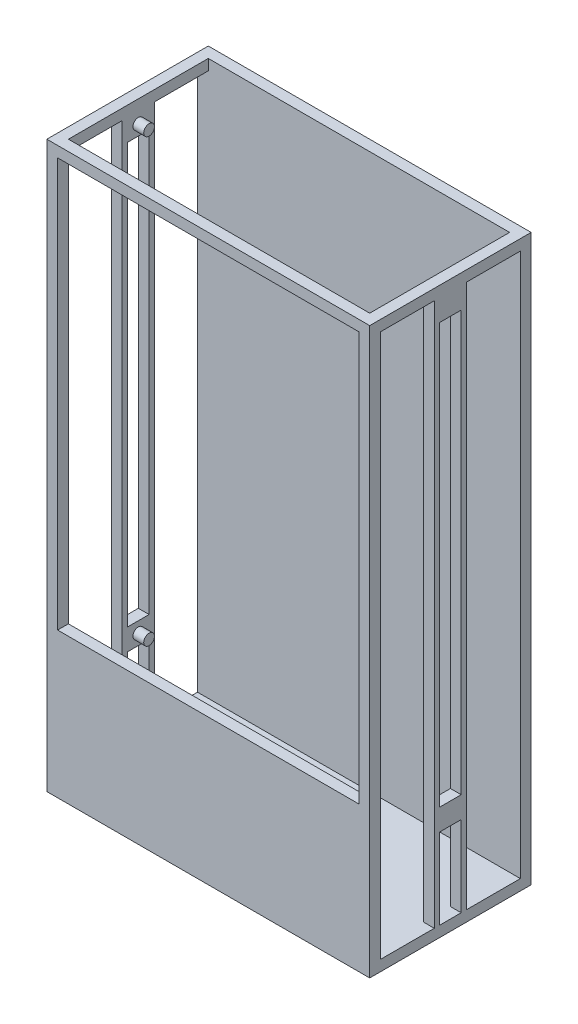
SolidWorks part; units mm, degrees
ref_plane "Front Plane" through (0, 0, 0) normal (0, 0, 1) x (1, 0, 0)
ref_plane "Top Plane" through (0, 0, 0) normal (0, 1, 0) x (1, 0, 0)
ref_plane "Right Plane" through (0, 0, 0) normal (1, 0, 0) x (0, 0, -1)
sketch "Sketch1" plane through (0, 0, 0) normal (0, 0, 1) x (1, 0, 0)
  line L1 (0, 0) -> (3000, 0)
  line L2 (0, 0) -> (0, -5000)
  line L3 (0, -5000) -> (3000, -5000)
  line L4 (3000, 0) -> (3000, -5000)
  dimension "D1" = 5000
  dimension "D2" = 3000
extrude "Boss-Extrude1" add sketch "Sketch1" along normal blind 100
sketch "Sketch2" plane through (0, 0, 100) normal (0, 0, 1) x (1, 0, 0)
  line L0 (0, 0) -> (0, -5000) construction
  line L1 (0, -4900) -> (3000, -4900)
  line L2 (0, -4900) -> (0, -5000)
  line L3 (0, -5000) -> (3000, -5000)
  line L4 (3000, -4900) -> (3000, -5000)
  dimension "D1" = 100
extrude "Boss-Extrude2" add sketch "Sketch2" along normal blind 1400
sketch "Sketch3" plane through (0, -4900, 0) normal (0, 1, 0) x (1, 0, 0)
  line L1 (0, -1500) -> (100, -1500)
  line L2 (0, -1500) -> (0, -1400)
  line L3 (0, -1400) -> (100, -1400)
  line L4 (100, -1500) -> (100, -1400)
  dimension "D1" = 100
  dimension "D2" = 100
extrude "Boss-Extrude3" add sketch "Sketch3" along normal blind 4900
sketch "Sketch4" plane through (0, -4900, 0) normal (0, 1, 0) x (1, 0, 0)
  line L1 (3000, -1500) -> (2900, -1500)
  line L2 (3000, -1500) -> (3000, -1400)
  line L3 (3000, -1400) -> (2900, -1400)
  line L4 (2900, -1500) -> (2900, -1400)
  dimension "D1" = 100
  dimension "D2" = 100
extrude "Boss-Extrude4" add sketch "Sketch4" along normal blind 4900
sketch "Sketch6" plane through (100, 0, 0) normal (1, 0, 0) x (0, 0, -1)
  line L0 (-1500, -5000) -> (-1500, 0) construction
  line L1 (-1400, -4900) -> (-1500, -4900)
  line L2 (-1400, -4900) -> (-1400, -3900)
  line L3 (-1400, -3900) -> (-1500, -3900)
  line L4 (-1500, -4900) -> (-1500, -3900)
  line L5 (-1500, -5000) -> (0, -5000) construction
  dimension "D1" = 1100
extrude "Boss-Extrude5" add sketch "Sketch6" along normal blind 2800
sketch "Sketch22" plane through (3000, 0, 0) normal (1, 0, 0) x (0, 0, -1)
  line L1 (-900, 0) -> (-600, 0)
  line L2 (-900, 0) -> (-900, -4900)
  line L3 (-900, -4900) -> (-600, -4900)
  line L4 (-600, 0) -> (-600, -4900)
  line L6 (-100, -4900) -> (-100, 0) construction
  line L7 (-100, 0) -> (0, 0) construction
  dimension "D1" = 500
  dimension "D2" = 800
  dimension "D3" = 4900
extrude "Boss-Extrude17" add sketch "Sketch22" against normal blind 100
sketch "Sketch23" plane through (0, 0, 0) normal (-1, 0, 0) x (0, 0, 1)
  line L1 (600, 0) -> (900, 0)
  line L2 (600, 0) -> (600, -4900)
  line L3 (600, -4900) -> (900, -4900)
  line L4 (900, 0) -> (900, -4900)
  line L9 (1500, 0) -> (1500, -5000) construction
  line L10 (1400, 0) -> (1500, 0) construction
  dimension "D1" = 600
  dimension "D2" = 900
  dimension "D3" = 4900
extrude "Boss-Extrude18" add sketch "Sketch23" against normal blind 100
sketch "Sketch24" plane through (0, 0, 0) normal (-1, 0, 0) x (0, 0, 1)
  line L1 (650, 0) -> (850, 0)
  line L2 (650, 0) -> (650, -4900)
  line L3 (650, -4900) -> (850, -4900)
  line L4 (850, 0) -> (850, -4900)
  line L8 (1400, 0) -> (1400, -4900) construction
  line L9 (1400, 0) -> (1500, 0) construction
  dimension "D1" = 550
  dimension "D2" = 750
  dimension "D3" = 4900
extrude "Cut-Extrude1" cut sketch "Sketch24" against normal through all
sketch "Sketch25" plane through (0, 0, 0) normal (-1, 0, 0) x (0, 0, 1)
  line L0 (650, 0) -> (650, -4900) construction
  line L1 (650, -4200) -> (850, -4200)
  line L2 (650, -4200) -> (650, -4400)
  line L3 (650, -4400) -> (850, -4400)
  line L4 (850, -4200) -> (850, -4400)
  line L5 (850, -4900) -> (850, 0) construction
  dimension "D1" = 500
extrude "Boss-Extrude19" add sketch "Sketch25" against normal blind 100
sketch "Sketch26" plane through (3000, 0, 0) normal (1, 0, 0) x (0, 0, -1)
  line L1 (-850, -4200) -> (-650, -4200)
  line L2 (-850, -4200) -> (-850, -4400)
  line L3 (-850, -4400) -> (-650, -4400)
  line L4 (-650, -4200) -> (-650, -4400)
extrude "Boss-Extrude20" add sketch "Sketch26" against normal blind 100
sketch "Sketch31" plane through (3000, 0, 0) normal (1, 0, 0) x (0, 0, -1)
  line L0 (-100, -4900) -> (-100, 0) construction
  line L1 (-1400, 0) -> (-100, 0)
  line L2 (-1400, 0) -> (-1400, -100)
  line L3 (-1400, -100) -> (-100, -100)
  line L4 (-100, 0) -> (-100, -100)
  dimension "D1" = 100
extrude "Boss-Extrude23" add sketch "Sketch31" against normal blind 100
sketch "Sketch33" plane through (0, 0, 0) normal (-1, 0, 0) x (0, 0, 1)
  line L1 (100, 0) -> (1400, 0)
  line L2 (100, 0) -> (100, -100)
  line L3 (100, -100) -> (1400, -100)
  line L4 (1400, 0) -> (1400, -100)
extrude "Boss-Extrude24" add sketch "Sketch33" against normal blind 100
sketch "Sketch34" plane through (2900, 0, 0) normal (-1, 0, 0) x (0, 0, 1)
  line L0 (1500, 0) -> (0, 0) construction
  line L1 (1400, 0) -> (1500, 0)
  line L2 (1400, 0) -> (1400, -100)
  line L3 (1400, -100) -> (1500, -100)
  line L4 (1500, 0) -> (1500, -100)
  line L5 (1500, 0) -> (1500, -5000) construction
sketch "Sketch43" plane through (0, 0, 0) normal (-1, 0, 0) x (0, 0, 1)
  line L0 (0, -5000) -> (1500, -5000)
  line L2 (0, -5000) -> (0, -5250)
  line L3 (0, -5250) -> (1500, -5250)
  line L4 (1500, -5000) -> (1500, -5250)
  line L23 (0, 0) -> (0, -5000) construction
  dimension "D1" = 250
  dimension "D2" = 1500
extrude "Boss-Extrude32" add sketch "Sketch43" against normal blind 3000
sketch "Sketch44" plane through (0, 0, 0) normal (-1, 0, 0) x (0, 0, 1)
  line L1 (100, -4900) -> (600, -4900)
  line L2 (100, -4900) -> (100, -5150)
  line L3 (100, -5150) -> (600, -5150)
  line L4 (600, -4900) -> (600, -5150)
  line L5 (0, -5250) -> (1500, -5250) construction
  dimension "D1" = 100
extrude "Cut-Extrude2" cut sketch "Sketch44" against normal through all
sketch "Sketch45" plane through (0, 0, 0) normal (-1, 0, 0) x (0, 0, 1)
  line L0 (0, -5250) -> (1500, -5250) construction
  line L1 (1400, -4900) -> (900, -4900)
  line L2 (1400, -4900) -> (1400, -5150)
  line L3 (1400, -5150) -> (900, -5150)
  line L4 (900, -4900) -> (900, -5150)
  dimension "D1" = 100
extrude "Cut-Extrude3" cut sketch "Sketch45" against normal blind 3000
sketch "Sketch46" plane through (0, 0, 0) normal (-1, 0, 0) x (0, 0, 1)
  line L0 (100, -5150) -> (600, -5150) construction
  line L1 (650, -4900) -> (850, -4900)
  line L2 (650, -4900) -> (650, -5150)
  line L3 (650, -5150) -> (850, -5150)
  line L4 (850, -4900) -> (850, -5150)
  line L6 (900, -5150) -> (900, -100) construction
  dimension "D1" = 50
extrude "Cut-Extrude4" cut sketch "Sketch46" against normal blind 3000
sketch "Sketch49" plane through (0, -4900, 0) normal (0, 1, 0) x (1, 0, 0)
  line L1 (100, -600) -> (2900, -600)
  line L2 (100, -600) -> (100, -900)
  line L3 (100, -900) -> (2900, -900)
  line L4 (2900, -600) -> (2900, -900)
extrude "Cut-Extrude5" cut sketch "Sketch49" against normal blind 250
extrude "Boss-Extrude25" add sketch "Sketch34" along normal blind 2800
sketch "Sketch36" plane through (0, 0, 0) normal (-1, 0, 0) x (0, 0, 1)
  line L0 (850, -4200) -> (850, -100) construction
  line L1 (650, -100) -> (850, -100)
  line L2 (650, -100) -> (650, -300)
  line L3 (650, -300) -> (850, -300)
  line L4 (850, -100) -> (850, -300)
  line L5 (850, -4200) -> (650, -4200) construction
extrude "Boss-Extrude26" add sketch "Sketch36" against normal blind 100
sketch "Sketch37" plane through (3000, 0, 0) normal (1, 0, 0) x (0, 0, -1)
  line L1 (-850, -100) -> (-650, -100)
  line L2 (-850, -100) -> (-850, -300)
  line L3 (-850, -300) -> (-650, -300)
  line L4 (-650, -100) -> (-650, -300)
extrude "Boss-Extrude27" add sketch "Sketch37" against normal blind 100
sketch "Sketch38" plane through (100, 0, 0) normal (1, 0, 0) x (0, 0, -1)
  line L0 (-750, 0) -> (-750, -4964.2472) construction
  line L1 (-1500, 0) -> (0, 0) construction
  line L2 (-850, -4200) -> (-850, -4400) construction
  line L3 (-850, -4300) -> (-600, -4300) construction
  line L4 (-600, -5150) -> (-600, -100) construction
  circle A0 centre (-750, -4300) radius 50
  dimension "D1" = 100
extrude "Boss-Extrude28" add sketch "Sketch38" along normal blind 100 contours A0
sketch "Sketch39" plane through (100, 0, 0) normal (1, 0, 0) x (0, 0, -1)
  line L0 (-750, 0) -> (-750, -300) construction
  line L1 (-1500, 0) -> (0, 0) construction
  line L2 (-850, -300) -> (-650, -300) construction
  line L3 (-850, -300) -> (-850, -100) construction
  line L4 (-850, -200) -> (-628.1086, -200) construction
  line L6 (-850, -4900) -> (-900, -4900) construction
  circle A0 centre (-750, -200) radius 50
  dimension "D1" = 100
  dimension "D2" = 4700
extrude "Boss-Extrude29" add sketch "Sketch39" along normal blind 100
sketch "Sketch40" plane through (2900, 0, 0) normal (-1, 0, 0) x (0, 0, 1)
  line L0 (750, 0) -> (750, -300) construction
  line L1 (1500, 0) -> (0, 0) construction
  line L2 (650, -300) -> (850, -300) construction
  line L3 (600, -100) -> (600, -300) construction
  line L4 (600, -100) -> (600, -5150) construction
  line L5 (600, -200) -> (900, -200) construction
  line L6 (900, -5150) -> (900, -100) construction
  circle A0 centre (750, -200) radius 50
  dimension "D1" = 100
extrude "Boss-Extrude30" add sketch "Sketch40" along normal blind 100
sketch "Sketch42" plane through (2900, 0, 0) normal (-1, 0, 0) x (0, 0, 1)
  line L0 (650, -4200) -> (650, -4400) construction
  line L1 (650, -4300) -> (941.5743, -4300) construction
  line L2 (750, -4200) -> (750, -4400) construction
  line L3 (850, -4200) -> (650, -4200) construction
  line L4 (650, -4400) -> (850, -4400) construction
  circle A0 centre (750, -4300) radius 50
  dimension "D1" = 100
extrude "Boss-Extrude31" add sketch "Sketch42" along normal blind 100
